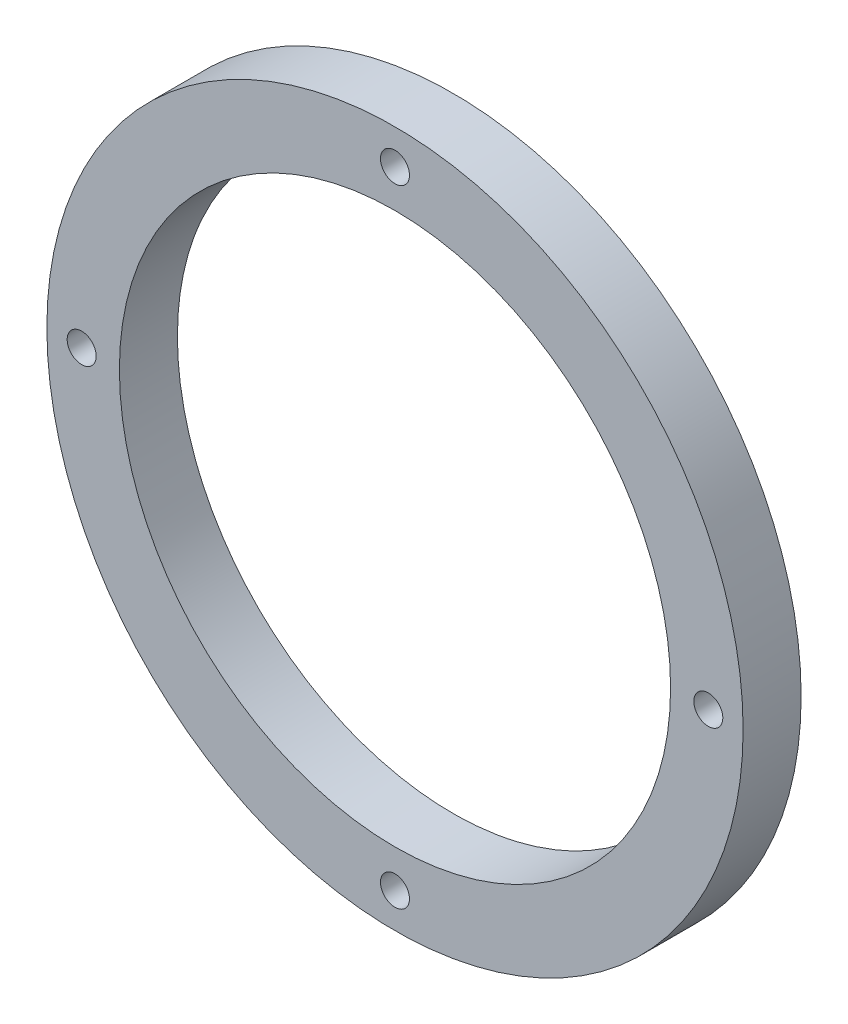
SolidWorks part; units mm, degrees
ref_plane "Спереди" through (0, 0, 0) normal (0, 0, 1) x (1, 0, 0)
ref_plane "Сверху" through (0, 0, 0) normal (0, 1, 0) x (1, 0, 0)
ref_plane "Справа" through (0, 0, 0) normal (1, 0, 0) x (0, 0, -1)
other "Configuration Table"
sketch "Eskiz_kontur" plane through (0, 0, 0) normal (0, 0, 1) x (1, 0, 0)
  circle A0 centre (0, 0) radius 30
extrude "Plastina" add sketch "Eskiz_kontur" along normal blind 5
sketch "Eskiz_otverstiya" plane through (0, 0, 0) normal (0, 0, 1) x (1, 0, 0)
  circle A0 centre (0, -27) radius 1.25
  circle A1 centre (-27, 0) radius 1.25
  circle A2 centre (0, 0) radius 23.75
  circle A3 centre (27, 0) radius 1.25
  circle A4 centre (0, 27) radius 1.25
  dimension "d1" = 2.5
  dimension "d2" = 2.5
  dimension "d3" = 47.5
  dimension "d4" = 2.5
  dimension "d5" = 2.5
extrude "Otverstiya" cut sketch "Eskiz_otverstiya" against normal through all and the other way through all
equation "\"T3\" = 3"
equation "\"T5\" = 5"
equation "\"D_M3\" = 3.3"
equation "\"D_M2\" = 2.2"
equation "\"D_M3_TAP\" = 2.5"
equation "\"D_M4\" = 4.5"
equation "\"L1\" = 100"
equation "\"L2\" = 100"
equation "\"D1@Plastina\" = \"T5\""
equation "\"d1@Eskiz_otverstiya\" = \"D_M3_TAP\""
equation "\"d2@Eskiz_otverstiya\" = \"D_M3_TAP\""
equation "\"d4@Eskiz_otverstiya\" = \"D_M3_TAP\""
equation "\"d5@Eskiz_otverstiya\" = \"D_M3_TAP\""
